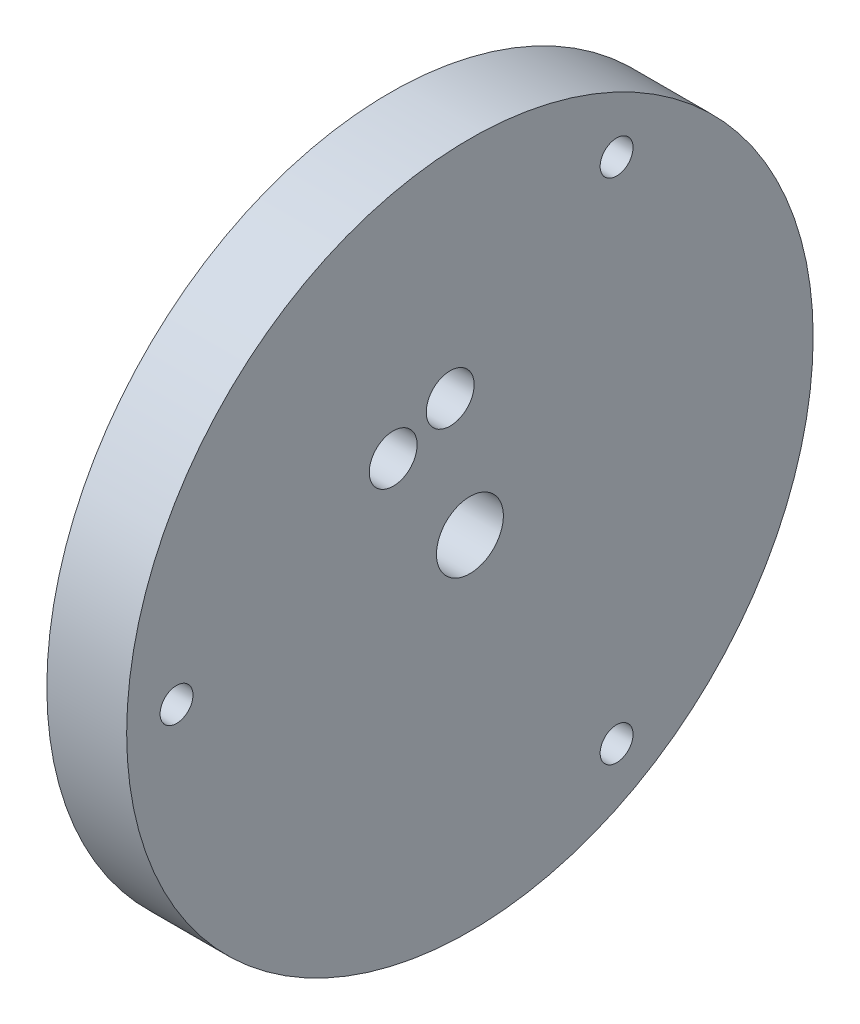
SolidWorks part; units mm, degrees
ref_plane "Front Plane" through (0, 0, 0) normal (0, 0, 1) x (1, 0, 0)
ref_plane "Top Plane" through (0, 0, 0) normal (0, 1, 0) x (1, 0, 0)
ref_plane "Right Plane" through (0, 0, 0) normal (1, 0, 0) x (0, 0, -1)
sketch "Axial profile (mm)" plane through (0, 0, 0) normal (0, 0, 1) x (1, 0, 0)
  line L0 (-110, 0) -> (75, 0) construction
  line L1 (148.7, 3.35) -> (156.7, 3.35)
  line L2 (156.7, 3.35) -> (156.7, 34.4)
  line L3 (156.7, 34.4) -> (148.7, 34.4)
  line L4 (148.7, 34.4) -> (148.7, 3.35)
revolve "Full revolution" add sketch "Axial profile (mm)" angle 360 about L0
sketch "Sketch2" plane through (0, 0, 0) normal (1, 0, 0) x (0, 0, -1)
  circle A0 centre (-1.9774, 12.8487) radius 2.4
  circle A1 centre (-7.6872, 10.4836) radius 2.4
  circle A2 centre (-29.4, 0) radius 1.65
  circle A3 centre (14.7, -25.4611) radius 1.65
  circle A4 centre (14.7, 25.4611) radius 1.65
extrude "Axial holes" cut sketch "Sketch2" against normal through all and the other way through all
